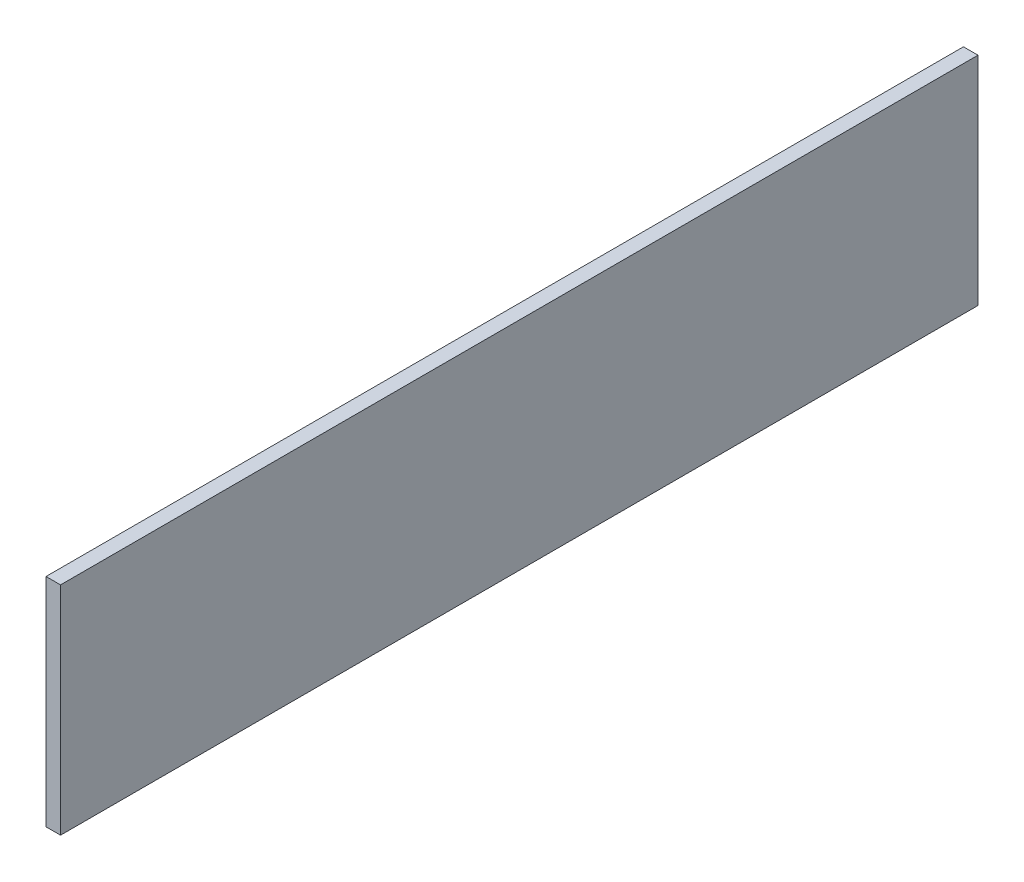
SolidWorks part; units mm, degrees
ref_plane "Front Plane" through (0, 0, 0) normal (0, 0, 1) x (1, 0, 0)
ref_plane "Top Plane" through (0, 0, 0) normal (0, 1, 0) x (1, 0, 0)
ref_plane "Right Plane" through (0, 0, 0) normal (1, 0, 0) x (0, 0, -1)
other "Configuration Table"
sketch "Sketch1" plane through (0, 0, 0) normal (0, 0, 1) x (1, 0, 0)
  line L1 (1338, 1469) -> (1350, 1469)
  line L2 (1338, 1469) -> (1338, 1648)
  line L3 (1338, 1648) -> (1350, 1648)
  line L4 (1350, 1469) -> (1350, 1648)
extrude "DET_bolme_saci_sag_1" add sketch "Sketch1" against normal blind 757.5 separate body
